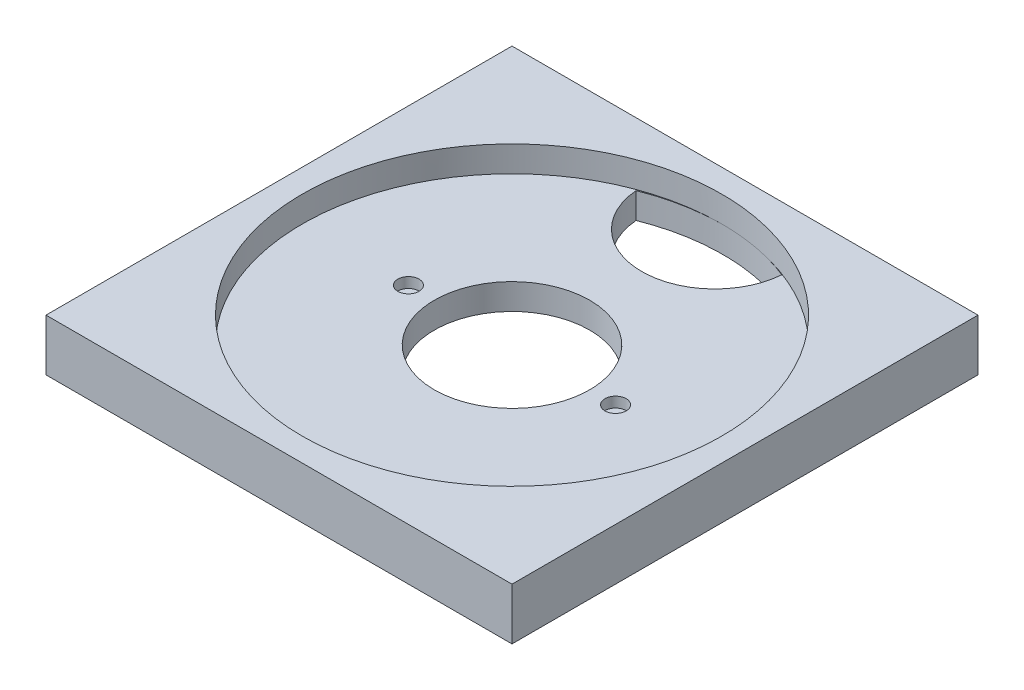
SolidWorks part; units mm, degrees
ref_plane "Front Plane" through (0, 0, 0) normal (0, 0, 1) x (1, 0, 0)
ref_plane "Top Plane" through (0, 0, 0) normal (0, 1, 0) x (1, 0, 0)
ref_plane "Right Plane" through (0, 0, 0) normal (1, 0, 0) x (0, 0, -1)
sketch "Sketch1" plane through (0, 0, 0) normal (0, 1, 0) x (1, 0, 0)
  line L2 (0, -45) -> (-45, -45)
  line L3 (-45, -45) -> (-45, 45)
  line L4 (-45, 45) -> (0, 45)
  line L5 (0, 45) -> (45, 45)
  line L6 (45, 45) -> (45, -45)
  line L7 (45, -45) -> (0, -45)
extrude "Boss-Extrude1" add sketch "Sketch1" along normal blind 10
sketch "Sketch2" plane through (0, 10, 0) normal (0, 1, 0) x (1, 0, 0)
  circle A0 centre (0, 0) radius 40.5
extrude "Cut-Extrude1" cut sketch "Sketch2" against normal blind 5 contours A0
sketch "Sketch4" plane through (0, 5, 0) normal (0, 1, 0) x (1, 0, 0)
  circle A2 centre (-20, 0) radius 2.05
  circle A3 centre (20, 0) radius 2.05
extrude "Cut-Extrude2" cut sketch "Sketch4" against normal blind 2
sketch "Sketch5" plane through (0, 5, 0) normal (0, 1, 0) x (1, 0, 0)
  circle A0 centre (0, 0) radius 15
extrude "Cut-Extrude3" cut sketch "Sketch5" against normal through all
sketch "Sketch7" plane through (0, 5, 0) normal (0, 1, 0) x (1, 0, 0)
  arc A0 (-13.8415, 37.8005) -> (14.3106, 37.8005) centre (0.2345, 38.9392) ccw
  arc A1 (-13.8415, 37.8005) -> (14.3106, 37.8005) centre (0.2345, 2.5037) cw
extrude "Cut-Extrude4" cut sketch "Sketch7" against normal blind 36 contours A0 A1
